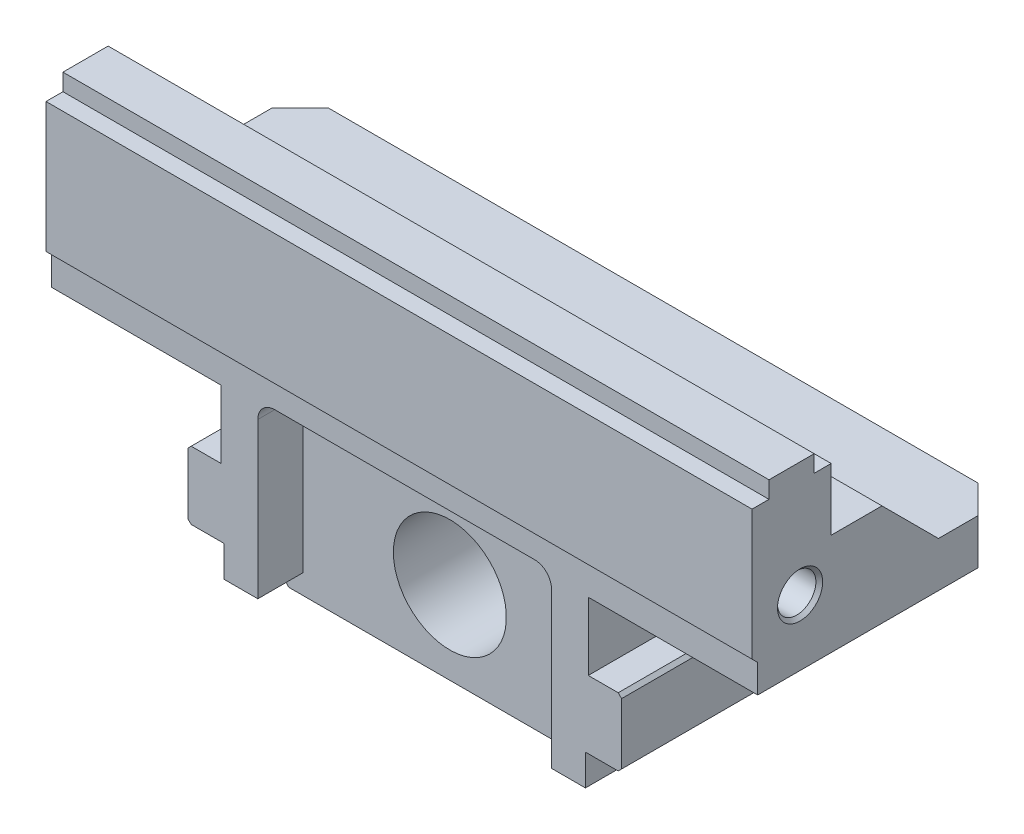
SolidWorks part; units mm, degrees
ref_plane "Front Plane" through (0, 0, 0) normal (0, 0, 1) x (1, 0, 0)
ref_plane "Top Plane" through (0, 0, 0) normal (0, 1, 0) x (1, 0, 0)
ref_plane "Right Plane" through (0, 0, 0) normal (1, 0, 0) x (0, 0, -1)
ref_plane "Plane1" through (0, 0, -23) normal (0, 0, -1) x (-1, 0, 0)
sketch "Sketch1" plane through (0, 0, -23) normal (0, 0, -1) x (-1, 0, 0)
  line L0 (-62.5, 24) -> (62.5, 24)
  line L1 (62.5, 24) -> (62.5, 89)
  line L2 (62.5, 89) -> (-62.5, 89)
  line L3 (-62.5, 89) -> (-62.5, 24)
extrude "Boss-Extrude1" add sketch "Sketch1" against normal blind 47
sketch "Sketch2" plane through (-62.5, 0, 0) normal (-1, 0, 0) x (0, 0, 1)
  line L0 (24, 24) -> (24, 63)
  line L1 (24, 63) -> (23, 62)
  line L2 (23, 62) -> (23, 24)
  line L3 (23, 24) -> (24, 24)
extrude "Cut-Extrude1" cut sketch "Sketch2" against normal through all
sketch "Sketch3" plane through (0, 0, -23) normal (0, 0, -1) x (-1, 0, 0)
  line L0 (62.5, 57) -> (32.5, 57)
  line L1 (32.5, 57) -> (32.5, 24)
  line L2 (32.5, 24) -> (62.5, 24)
  line L3 (62.5, 24) -> (62.5, 57)
extrude "Cut-Extrude2" cut sketch "Sketch3" against normal through all
sketch "Sketch4" plane through (-32.5, 0, 0) normal (-1, 0, 0) x (0, 0, 1)
  line L0 (23, 45) -> (23, 24)
  line L1 (23, 24) -> (-23, 24)
  line L2 (-23, 24) -> (-23, 45)
  line L3 (-23, 45) -> (23, 45)
extrude "Boss-Extrude2" add sketch "Sketch4" along normal blind 5.9
sketch "Sketch5" plane through (0, 0, -23) normal (0, 0, -1) x (-1, 0, 0)
  line L0 (-32.5, 24) -> (-32.5, 57)
  line L1 (-32.5, 57) -> (-62.5, 57)
  line L2 (-62.5, 57) -> (-62.5, 24)
  line L3 (-62.5, 24) -> (-32.5, 24)
extrude "Cut-Extrude3" cut sketch "Sketch5" against normal through all
sketch "Sketch6" plane through (32.5, 0, 0) normal (1, 0, 0) x (0, 0, -1)
  line L0 (-23, 24) -> (-23, 45)
  line L1 (-23, 45) -> (23, 45)
  line L2 (23, 45) -> (23, 24)
  line L3 (23, 24) -> (-23, 24)
extrude "Boss-Extrude3" add sketch "Sketch6" along normal blind 5.9
sketch "Sketch7" plane through (0, 0, 23) normal (0, 0, 1) x (1, 0, 0)
  line L0 (32, 33) -> (32, 24)
  line L1 (32, 24) -> (38.4, 24)
  line L2 (38.4, 24) -> (38.4, 33)
  line L3 (38.4, 33) -> (32, 33)
extrude "Cut-Extrude4" cut sketch "Sketch7" against normal through all
sketch "Sketch8" plane through (0, 0, 23) normal (0, 0, 1) x (1, 0, 0)
  line L0 (-32, 33) -> (-38.4, 33)
  line L1 (-38.4, 33) -> (-38.4, 24)
  line L2 (-38.4, 24) -> (-32, 24)
  line L3 (-32, 24) -> (-32, 33)
extrude "Cut-Extrude5" cut sketch "Sketch8" against normal through all
sketch "Sketch9" plane through (32, 0, 0) normal (1, 0, 0) x (0, 0, -1)
  line L0 (-15, 24) -> (-15, 27.5)
  line L1 (-15, 27.5) -> (-23, 27.5)
  line L2 (-23, 27.5) -> (-23, 24)
  line L3 (-23, 24) -> (-15, 24)
extrude "Cut-Extrude6" cut sketch "Sketch9" against normal through all
sketch "Sketch10" plane through (0, 0, 23) normal (0, 0, 1) x (1, 0, 0)
  line L0 (-26, 58) -> (-26, 27.5)
  line L1 (-26, 27.5) -> (26, 27.5)
  line L2 (26, 27.5) -> (26, 58)
  line L3 (26, 58) -> (-26, 58)
extrude "Cut-Extrude7" cut sketch "Sketch10" against normal blind 8
sketch "Sketch11" plane through (32, 0, 0) normal (1, 0, 0) x (0, 0, -1)
  line L0 (15, 27.5) -> (15, 24)
  line L1 (15, 24) -> (23, 24)
  line L2 (23, 24) -> (23, 27.5)
  line L3 (23, 27.5) -> (15, 27.5)
extrude "Cut-Extrude8" cut sketch "Sketch11" against normal through all
sketch "Sketch12" plane through (0, 0, -23) normal (0, 0, -1) x (-1, 0, 0)
  line L0 (26, 58) -> (-26, 58)
  line L1 (-26, 58) -> (-26, 27.5)
  line L2 (-26, 27.5) -> (26, 27.5)
  line L3 (26, 27.5) -> (26, 58)
extrude "Cut-Extrude9" cut sketch "Sketch12" against normal blind 8
sketch "Sketch13" plane through (-62.5, 0, 0) normal (-1, 0, 0) x (0, 0, 1)
  line L0 (-23, 89) -> (-23, 75)
  line L1 (-23, 75) -> (10, 75)
  line L2 (10, 75) -> (10, 89)
  line L3 (10, 89) -> (-23, 89)
extrude "Cut-Extrude10" cut sketch "Sketch13" against normal through all
sketch "Sketch14" plane through (-62.5, 0, 0) normal (-1, 0, 0) x (0, 0, 1)
  line L0 (-23, 75) -> (-23, 65)
  line L1 (-23, 65) -> (-9, 65)
  line L2 (-9, 65) -> (1, 75)
  line L3 (1, 75) -> (-23, 75)
extrude "Cut-Extrude11" cut sketch "Sketch14" against normal through all
sketch "Sketch15" plane through (-62.5, 0, 0) normal (-1, 0, 0) x (0, 0, 1)
  line L0 (10, 89) -> (10, 86)
  line L1 (10, 86) -> (13, 86)
  line L2 (13, 86) -> (13, 89)
  line L3 (13, 89) -> (10, 89)
extrude "Cut-Extrude12" cut sketch "Sketch15" against normal through all
sketch "Sketch16" plane through (-62.5, 0, 0) normal (-1, 0, 0) x (0, 0, 1)
  line L0 (24, 89) -> (21, 89)
  line L1 (21, 89) -> (21, 86)
  line L2 (21, 86) -> (24, 86)
  line L3 (24, 86) -> (24, 89)
extrude "Cut-Extrude13" cut sketch "Sketch16" against normal through all
hole_wizard "Ø6.8 (6.8) Diameter Hole1" positions "Sketch18" profile "Sketch17" hole size "Ø6.8" standard "ANSI Metric"
sketch "Sketch18" plane through (-62.5, 0, 0) normal (-1, 0, 0) x (0, 0, 1)
  point P0 (15.5, 68.6)
sketch "Sketch17" plane through (-62.5, 68.6, 15.5) normal (0, 1, 0) x (0, 0, 1)
  line L0 (0, 0) -> (0, 24.0429)
  line L1 (0, 24.0429) -> (3.4, 22)
  line L2 (3.4, 22) -> (3.4, 0)
  line L5 (3.4, 0) -> (0, 0)
  line L10 (0, 24.0429) -> (-3.4, 22) construction
  line L11 (0, -6.35) -> (0, 107.95) construction
  dimension "Hole Dia." = 6.8
  dimension "Hole Depth" = 22
  dimension "Drill Angle" = 118
hole_wizard "Ø6.8 (6.8) Diameter Hole2" positions "Sketch20" profile "Sketch19" hole size "Ø6.8" standard "ANSI Metric"
sketch "Sketch20" plane through (62.5, 0, 0) normal (1, 0, 0) x (0, 0, -1)
  point P0 (-15.5, 68.6)
sketch "Sketch19" plane through (62.5, 68.6, 15.5) normal (0, 1, 0) x (0, 0, -1)
  line L0 (0, 0) -> (0, 24.0429)
  line L1 (0, 24.0429) -> (3.4, 22)
  line L2 (3.4, 22) -> (3.4, 0)
  line L5 (3.4, 0) -> (0, 0)
  line L10 (0, 24.0429) -> (-3.4, 22) construction
  line L11 (0, -6.35) -> (0, 107.95) construction
  dimension "Hole Dia." = 6.8
  dimension "Hole Depth" = 22
  dimension "Drill Angle" = 118
hole_wizard "Ø20.0 (20) Diameter Hole1" positions "Sketch22" profile "Sketch21" hole size "Ø20.0" standard "ANSI Metric"
sketch "Sketch22" plane through (0, 0, -15) normal (0, 0, -1) x (-1, 0, 0)
  point P0 (0, 38.65)
sketch "Sketch21" plane through (0, 38.65, -15) normal (1, 0, 0) x (0, 1, 0)
  line L0 (0, 0) -> (0, 39)
  line L1 (0, 39) -> (10, 39)
  line L2 (10, 39) -> (10, 0)
  line L5 (10, 0) -> (0, 0)
  line L11 (0, -6.35) -> (0, 107.95) construction
  dimension "Thru Hole Dia." = 20
  dimension "Thru Hole Depth" = 39
chamfer "Chamfer1" distance 0.6 angle 45 6 edges at (-38.4, 45, 0) (38.4, 33, 0) (-38.4, 33, 0) (-62.5, 68.6, 18.9) (38.4, 45, 0) (62.5, 68.6, 12.1)
chamfer "Chamfer2" distance 2 angle 45 1 edges at (0, 65, -23)
chamfer "Chamfer3" distance 3.5 angle 45 2 edges at (32, 24, 0) (-32, 24, 0)
chamfer "Chamfer4" distance 7 angle 45 2 edges at (-62.5, 60, -23) (62.5, 60, -23)
fillet "Fillet1" radius 3 4 edges at (26, 58, -19) (-26, 58, -19) (26, 58, 19) (-26, 58, 19)
